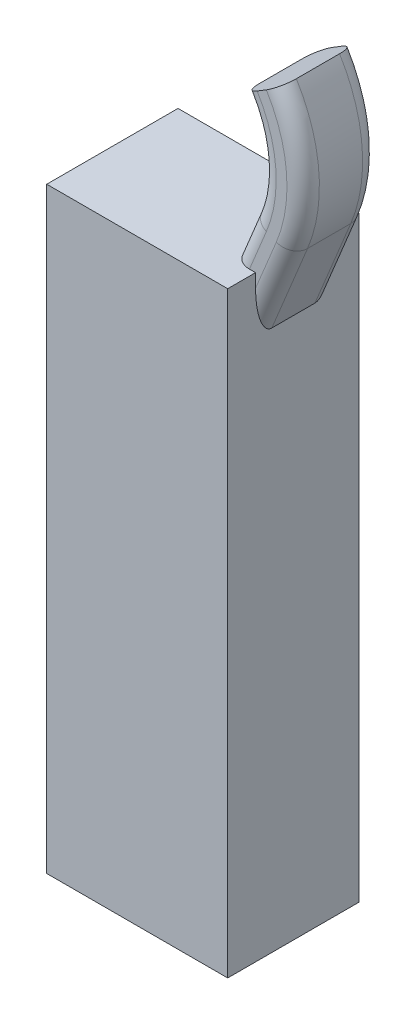
SolidWorks part; units mm, degrees
ref_plane "Front" through (0, 0, 0) normal (0, 0, 1) x (1, 0, 0)
ref_plane "Top" through (0, 0, 0) normal (0, 1, 0) x (1, 0, 0)
ref_plane "Right" through (0, 0, 0) normal (1, 0, 0) x (0, 0, -1)
sketch "Sketch1" plane through (0, 0, 0) normal (0, 0, 1) x (1, 0, 0)
  line L1 (-16.75, -55.25) -> (16.75, -55.25)
  line L2 (-16.75, -55.25) -> (-16.75, 55.25)
  line L3 (-16.75, 55.25) -> (16.75, 55.25)
  line L4 (16.75, -55.25) -> (16.75, 55.25)
  line L5 (-16.75, -55.25) -> (16.75, 55.25) construction
  line L6 (-16.75, 55.25) -> (16.75, -55.25) construction
  point P0 (0, 0)
  dimension "D1" = 33.5
  dimension "D2" = 110.5
extrude "Body" add sketch "Sketch1" along normal mid plane 24.3
sketch "Sketch2" plane through (0, 0, 0) normal (0, 0, 1) x (1, 0, 0)
  line L0 (10.9171, 41.2177) -> (19.6805, 62.4579)
  arc A0 (19.6805, 62.4579) -> (17.8981, 85.0348) centre (-3.4283, 71.9923) ccw
  point P4 (10.9171, 41.2177)
  point P5 (19.6805, 62.4579)
extrude "Cable" add sketch "Sketch2" along normal mid plane 14 thin thin type mid plane wall 8
fillet "Fillet1" radius 3 8 edges at (20.0641, 52.8998, -7) (20.0641, 52.8998, 7) (14.1812, 59.6167, -7) (14.1812, 59.6167, 7) (25.4802, 74.2745, -7) (25.4802, 74.2745, 7) (17.505, 73.6449, -7) (17.505, 73.6449, 7)
